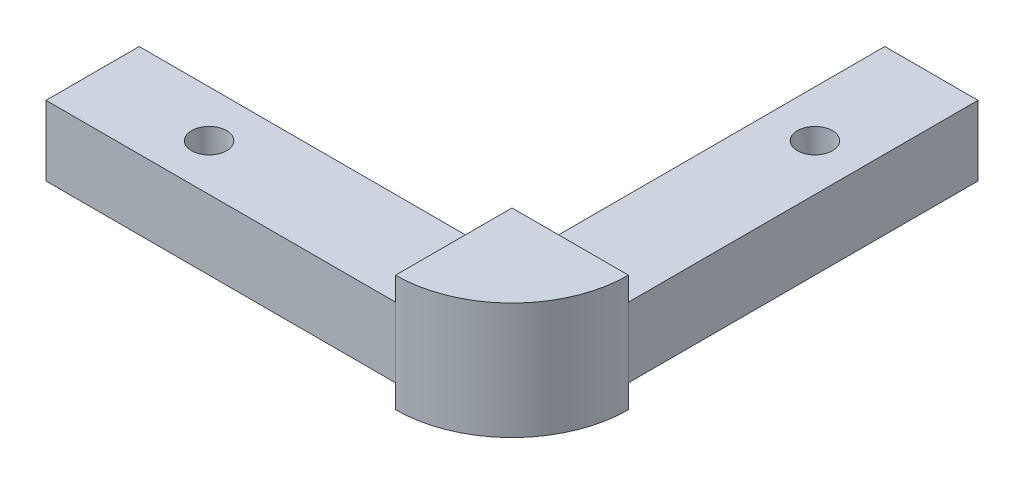
SolidWorks part; units mm, degrees
ref_plane "前视基准面" through (0, 0, 0) normal (0, 0, 1) x (1, 0, 0)
ref_plane "上视基准面" through (0, 0, 0) normal (0, 1, 0) x (1, 0, 0)
ref_plane "右视基准面" through (0, 0, 0) normal (1, 0, 0) x (0, 0, -1)
sketch "草图5" plane through (0, 0, 0) normal (0, 1, 0) x (1, 0, 0)
  line L1 (-34.3342, 14.7736) -> (-32.3342, 14.7736)
  line L2 (-34.3342, 14.7736) -> (-34.3342, 12.7736)
  line L6 (-24.3342, 14.7736) -> (-24.3342, 44.7736)
  line L7 (-24.3342, 44.7736) -> (-32.3342, 44.7736)
  line L8 (-32.3342, 14.7736) -> (-32.3342, 44.7736)
  line L9 (-34.3342, 4.7736) -> (-64.3342, 4.7736)
  line L11 (-34.3342, 12.7736) -> (-64.3342, 12.7736)
  line L12 (-64.3342, 4.7736) -> (-64.3342, 12.7736)
  arc A0 (-34.3342, 4.7736) -> (-24.3342, 14.7736) centre (-34.3342, 14.7736) ccw
  dimension "D1" = 30
  dimension "D3" = 10
  dimension "D2" = 30
  dimension "D4" = 8
  dimension "D5" = 8
  dimension "D6" = 2
  dimension "D7" = 2
extrude "凸台-拉伸5" add sketch "草图5" along normal blind 6
sketch "草图6" plane through (0, 6, 0) normal (0, 1, 0) x (1, 0, 0)
  line L5 (-34.3342, 14.7736) -> (-24.3342, 14.7736)
  line L6 (-34.3342, 14.7736) -> (-34.3342, 4.7736)
  arc A1 (-34.3342, 4.7736) -> (-24.3342, 14.7736) centre (-34.3342, 14.7736) ccw
extrude "凸台-拉伸7" add sketch "草图6" along normal blind 2 and the other way blind 8
sketch "草图7" plane through (0, 6, 0) normal (0, 1, 0) x (1, 0, 0)
  line L0 (-34.3342, 12.7736) -> (-34.3342, 4.7736) construction
  line L1 (-64.3342, 4.7736) -> (-34.3342, 4.7736) construction
  line L2 (-24.3342, 14.7736) -> (-24.3342, 44.7736) construction
  line L3 (-24.3342, 14.7736) -> (-32.3342, 14.7736) construction
  circle A0 centre (-54.3342, 8.7736) radius 1.5
  circle A1 centre (-28.3342, 34.7736) radius 1.5
  dimension "D1" = 20
  dimension "D3" = 4
  dimension "D2" = 4
  dimension "D4" = 20
extrude "切除-拉伸1" cut sketch "草图7" against normal blind 10
